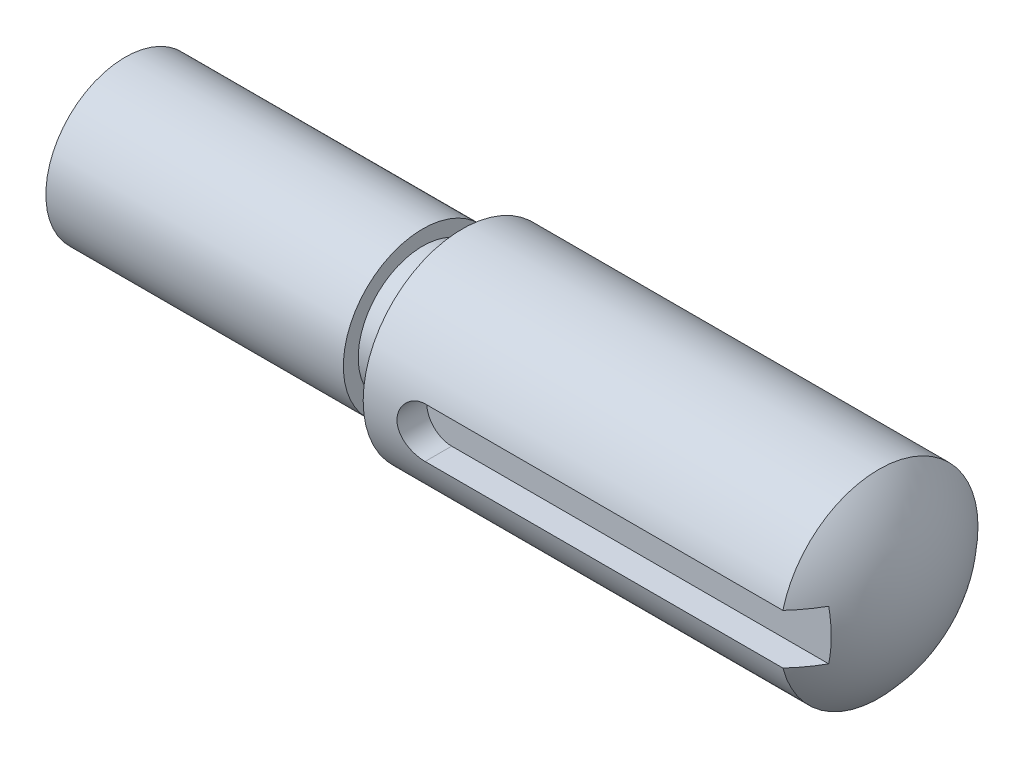
SolidWorks part; units mm, degrees
ref_plane "Plan de face" through (0, 0, 0) normal (0, 0, 1) x (1, 0, 0)
ref_plane "Plan de dessus" through (0, 0, 0) normal (0, 1, 0) x (1, 0, 0)
ref_plane "Plan de droite" through (0, 0, 0) normal (1, 0, 0) x (0, 0, -1)
sketch "Esquisse1" plane through (0, 0, 0) normal (0, 0, 1) x (1, 0, 0)
  line L0 (80, 0) -> (0, 0)
  line L1 (0, 0) -> (0, 8)
  line L2 (0, 8) -> (30, 8)
  line L3 (30, 8) -> (30, 6.5)
  line L4 (30, 6.5) -> (34, 6.5)
  line L5 (34, 6.5) -> (34, 10)
  line L6 (34, 10) -> (76, 10)
  arc A0 (76, 10) -> (80, 0) centre (65.5, 0) cw
  dimension "D1" = 8
  dimension "D2" = 6.5
  dimension "D3" = 4
  dimension "D4" = 34
  dimension "D5" = 10
  dimension "D6" = 46
  dimension "D7" = 4
revolve "Révolution1" add sketch "Esquisse1" angle 360 about L0
ref_plane "Plan1" through (0, 0, 10) normal (0, 0, 1) x (1, 0, 0)
sketch "Esquisse2" plane through (0, 0, 10) normal (0, 0, 1) x (1, 0, 0)
  line L0 (39.9247, 2.518) -> (89.3966, 2.518)
  line L1 (89.3966, 2.518) -> (89.3966, -2.5142)
  line L2 (89.3966, -2.5142) -> (39.9247, -2.5142)
  arc A0 (39.9247, -2.5142) -> (39.9247, 2.518) centre (39.9247, 0.0019) cw
extrude "Enlèv. mat.-Extru.1" cut sketch "Esquisse2" against normal blind 3
